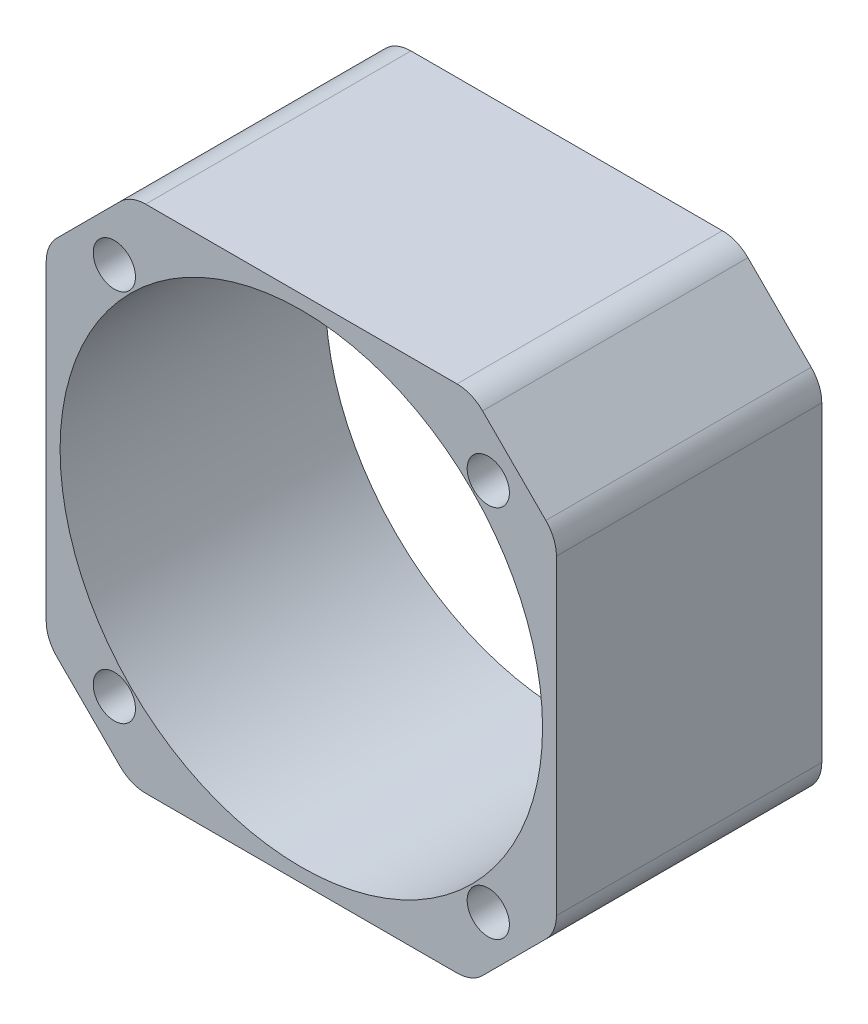
SolidWorks part; units mm, degrees
material "Żeliwo szare"
ref_plane "Płaszczyzna przednia" through (0, 0, 0) normal (0, 0, 1) x (1, 0, 0)
ref_plane "Płaszczyzna górna" through (0, 0, 0) normal (0, 1, 0) x (1, 0, 0)
ref_plane "Płaszczyzna prawa" through (0, 0, 0) normal (1, 0, 0) x (0, 0, -1)
sketch "Szkic1" plane through (0, 0, 0) normal (0, 0, 1) x (1, 0, 0)
  line L1 (-21.15, -21.15) -> (21.15, -21.15)
  line L2 (-21.15, -21.15) -> (-21.15, 21.15)
  line L3 (-21.15, 21.15) -> (21.15, 21.15)
  line L4 (21.15, -21.15) -> (21.15, 21.15)
  line L5 (0, 21.15) -> (0, -21.15) construction
  line L6 (-21.15, 0) -> (21.15, 0) construction
  point P0 (0, 0)
  dimension "D1" = 42.3
  dimension "D2" = 42.3
extrude "Dodanie-wyciągnięcie1" add sketch "Szkic1" along normal blind 22
chamfer "Sfazowanie1" distance 7 angle 45 4 edges at (-21.15, -21.15, 11) (21.15, -21.15, 11) (-21.15, 21.15, 11) (21.15, 21.15, 11)
fillet "Zaokrąglenie1" radius 3 8 edges at (14.15, -21.15, 11) (21.15, -14.15, 11) (21.15, 14.15, 11) (14.15, 21.15, 11) (-21.15, 14.15, 11) (-21.15, -14.15, 11) (-14.15, -21.15, 11) (-14.15, 21.15, 11)
sketch "Szkic2" plane through (0, 0, 22) normal (0, 0, 1) x (1, 0, 0)
  line L1 (-15.5, -15.5) -> (15.5, -15.5) construction
  line L2 (-15.5, -15.5) -> (-15.5, 15.5) construction
  line L3 (-15.5, 15.5) -> (15.5, 15.5) construction
  line L4 (15.5, -15.5) -> (15.5, 15.5) construction
  line L5 (0, 15.5) -> (0, -15.5) construction
  line L6 (-15.5, 0) -> (15.5, 0) construction
  circle A0 centre (0, 0) radius 20
  circle A1 centre (-15.5, 15.5) radius 1.75
  circle A2 centre (15.5, 15.5) radius 1.75
  circle A3 centre (15.5, -15.5) radius 1.75
  circle A4 centre (-15.5, -15.5) radius 1.75
  dimension "D1" = 40
  dimension "D4" = 3.5
  dimension "D2" = 31
  dimension "D3" = 31
extrude "Wytnij-wyciągnięcie1" cut sketch "Szkic2" against normal up to next
